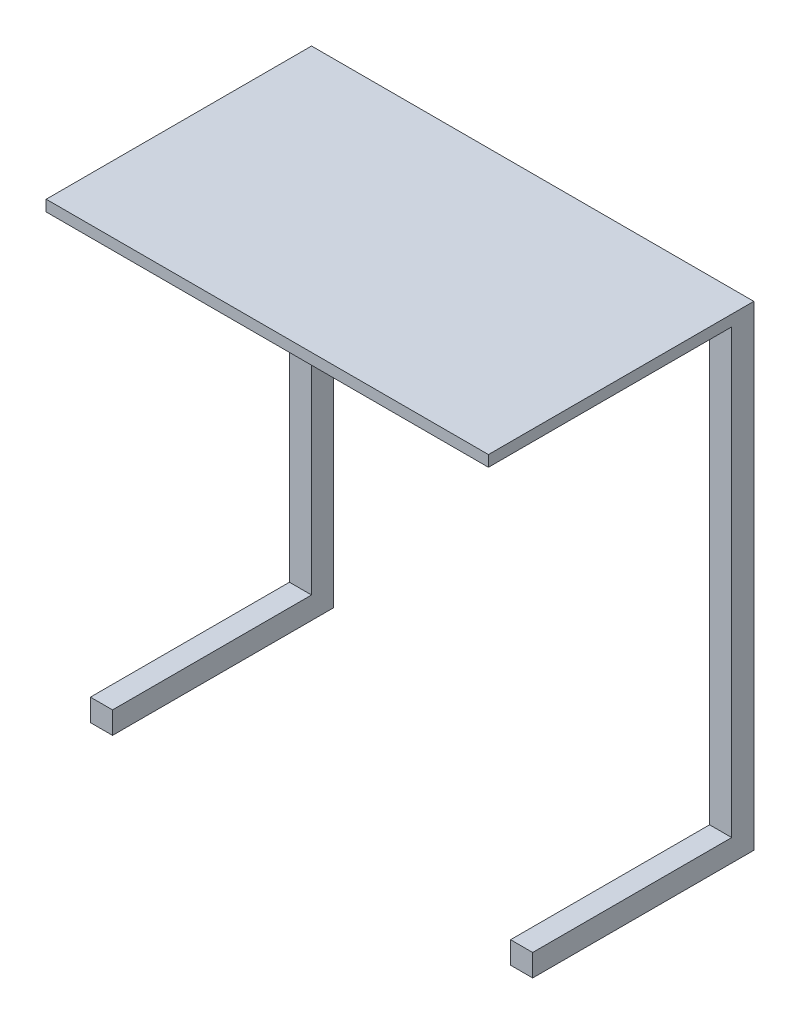
SolidWorks part; units mm, degrees
ref_plane "Front" through (0, 0, 0) normal (0, 0, 1) x (1, 0, 0)
ref_plane "Top" through (0, 0, 0) normal (0, 1, 0) x (1, 0, 0)
ref_plane "Right" through (0, 0, 0) normal (1, 0, 0) x (0, 0, -1)
sketch "Sketch1" plane through (0, 0, 0) normal (0, 1, 0) x (1, 0, 0)
  line L1 (-508, 304.8) -> (508, 304.8)
  line L2 (-508, 304.8) -> (-508, -304.8)
  line L3 (-508, -304.8) -> (508, -304.8)
  line L4 (508, 304.8) -> (508, -304.8)
  line L5 (-508, 304.8) -> (508, -304.8) construction
  line L6 (-508, -304.8) -> (508, 304.8) construction
  point P0 (0, 0)
  dimension "D1" = 609.6
  dimension "D2" = 1016
extrude "Boss-Extrude1" add sketch "Sketch1" along normal blind 25.4
sketch "Sketch2" plane through (0, 0, 0) normal (0, 1, 0) x (1, 0, 0)
  line L1 (-508, 304.8) -> (-457.2, 304.8)
  line L2 (-508, 304.8) -> (-508, 254)
  line L3 (-508, 254) -> (-457.2, 254)
  line L4 (-457.2, 304.8) -> (-457.2, 254)
  line L5 (508, 304.8) -> (457.2, 304.8)
  line L6 (508, 304.8) -> (508, 254)
  line L7 (508, 254) -> (457.2, 254)
  line L8 (457.2, 304.8) -> (457.2, 254)
  dimension "D1" = 50.8
extrude "Boss-Extrude2" add sketch "Sketch2" against normal blind 1016
sketch "Sketch3" plane through (0, -1016, 0) normal (0, -1, 0) x (-1, 0, 0)
  line L1 (508, 304.8) -> (457.2, 304.8)
  line L2 (508, 304.8) -> (508, -203.2)
  line L3 (508, -203.2) -> (457.2, -203.2)
  line L4 (457.2, 304.8) -> (457.2, -203.2)
  line L5 (457.2, 254) -> (457.2, 304.8) construction
  line L6 (-508, 304.8) -> (-457.2, 304.8) construction
  line L7 (-508, 304.8) -> (-457.2, 304.8)
  line L8 (-508, 304.8) -> (-508, -203.2)
  line L9 (-508, -203.2) -> (-457.2, -203.2)
  line L10 (-457.2, 304.8) -> (-457.2, -203.2)
  line L11 (-457.2, 304.8) -> (-457.2, 254) construction
  dimension "D1" = 508
extrude "Boss-Extrude3" add sketch "Sketch3" along normal blind 50.8
